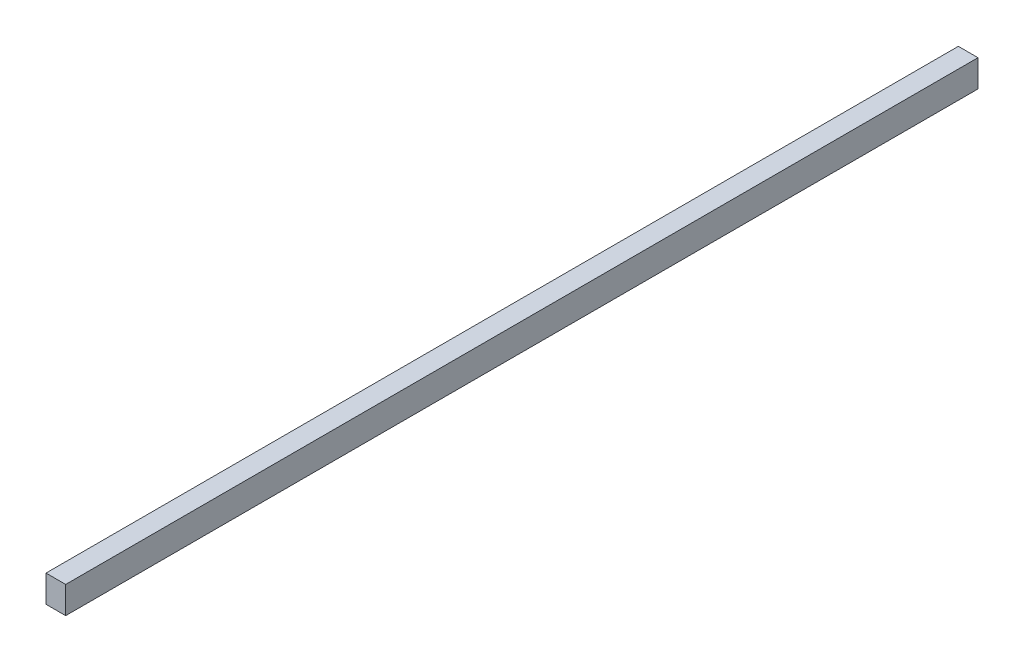
SolidWorks part; units mm, degrees
ref_plane "Front Plane" through (0, 0, 0) normal (0, 0, 1) x (1, 0, 0)
ref_plane "Top Plane" through (0, 0, 0) normal (0, 1, 0) x (1, 0, 0)
ref_plane "Right Plane" through (0, 0, 0) normal (1, 0, 0) x (0, 0, -1)
sketch "Sketch1" plane through (0, 0, 0) normal (0, 0, 1) x (1, 0, 0)
  line L1 (0, 0) -> (7.9375, 0)
  line L2 (0, 0) -> (0, 10.922)
  line L3 (0, 10.922) -> (7.9375, 10.922)
  line L4 (7.9375, 0) -> (7.9375, 10.922)
  dimension "D1" = 7.9375
  dimension "D2" = 10.922
extrude "Boss-Extrude1" add sketch "Sketch1" against normal blind 368.046
